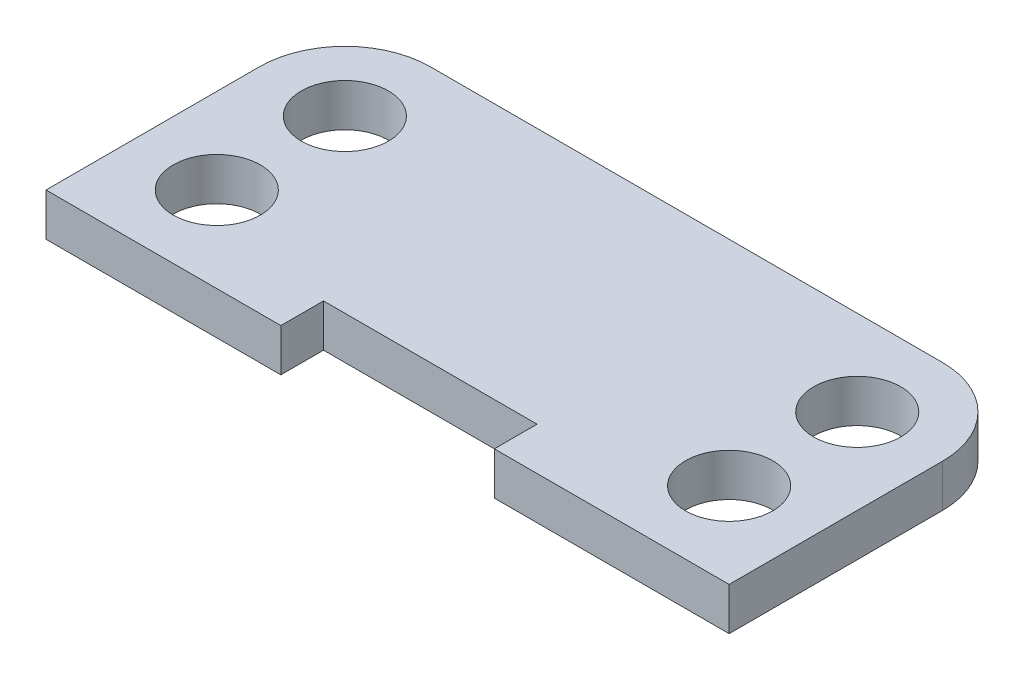
SolidWorks part; units mm, degrees
material "6061 Alloy"
ref_plane "Front Plane" through (0, 0, 0) normal (0, 0, 1) x (1, 0, 0)
ref_plane "Top Plane" through (0, 0, 0) normal (0, 1, 0) x (1, 0, 0)
ref_plane "Right Plane" through (0, 0, 0) normal (1, 0, 0) x (0, 0, -1)
sketch "Sketch1" plane through (0, 0, 0) normal (0, 1, 0) x (1, 0, 0)
  line L0 (38.1, 38.1) -> (-38.1, 38.1)
  line L1 (-50.8, 25.4) -> (-50.8, -6.35)
  line L2 (-50.8, -6.35) -> (-15.875, -6.35)
  line L3 (-15.875, -6.35) -> (-15.875, 0)
  line L4 (-15.875, 0) -> (15.875, 0)
  line L5 (15.875, 0) -> (15.875, -6.35)
  line L6 (15.875, -6.35) -> (50.8, -6.35)
  line L7 (50.8, -6.35) -> (50.8, 25.4)
  arc A0 (38.1, 38.1) -> (50.8, 25.4) centre (38.1, 25.4) cw
  arc A1 (-38.1, 38.1) -> (-50.8, 25.4) centre (-38.1, 25.4) ccw
  circle A2 centre (-38.1, 25.4) radius 6.477
  circle A3 centre (-38.1, 6.35) radius 6.477
  circle A4 centre (38.1, 25.4) radius 6.477
  circle A5 centre (38.1, 6.35) radius 6.477
  point P12 (50.8, 38.1)
  point P15 (-50.8, 38.1)
  dimension "D7" = 12.7
  dimension "D8" = 19.05
  dimension "D9" = 12.954
  dimension "D1" = 31.75
  dimension "D2" = 15.875
  dimension "D3" = 6.35
  dimension "D4" = 44.45
  dimension "D5" = 101.6
  dimension "D6" = 50.8
extrude "Boss-Extrude1" add sketch "Sketch1" along normal mid plane 6.35
